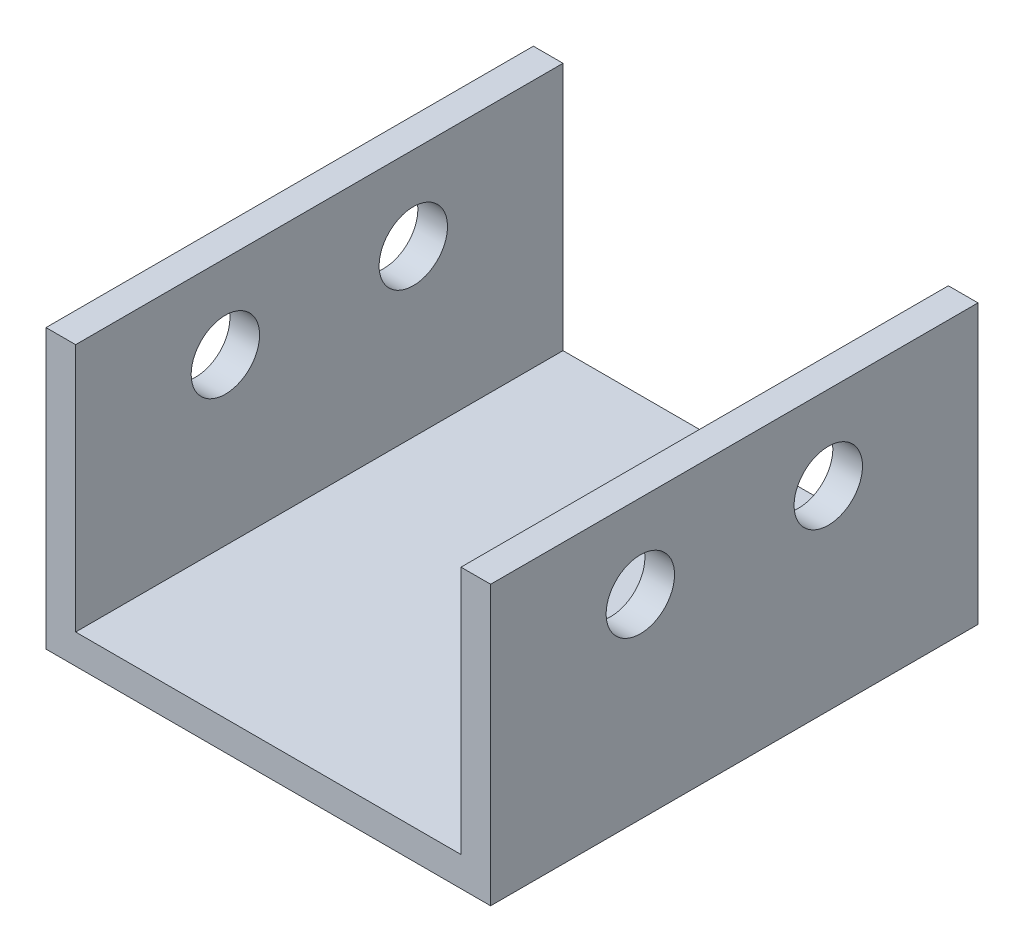
SolidWorks part; units mm, degrees
ref_plane "Front Plane" through (0, 0, 0) normal (0, 0, 1) x (1, 0, 0)
ref_plane "Top Plane" through (0, 0, 0) normal (0, 1, 0) x (1, 0, 0)
ref_plane "Right Plane" through (0, 0, 0) normal (1, 0, 0) x (0, 0, -1)
sketch "Sketch1" plane through (0, 0, 0) normal (0, 0, 1) x (1, 0, 0)
  line L0 (-26, 0) -> (26, 0)
  line L1 (26, 0) -> (26, 32.5714)
  line L2 (26, 32.5714) -> (22.5333, 32.5714)
  line L3 (22.5333, 32.5714) -> (22.5333, 3.4667)
  line L4 (22.5333, 3.4667) -> (-22.5333, 3.4667)
  line L5 (-22.5333, 3.4667) -> (-22.5333, 32.5714)
  line L6 (-22.5333, 32.5714) -> (-26, 32.5714)
  line L7 (-26, 32.5714) -> (-26, 0)
  line L9 (26, 0) -> (22.5333, 0) construction
  line L10 (26, 0) -> (26, 3.4667) construction
  line L11 (26, 3.4667) -> (22.5333, 3.4667) construction
  line L12 (22.5333, 0) -> (22.5333, 3.4667) construction
  point P4 (0, 0)
  dimension "D1" = 3.4667
  dimension "D2" = 32.5714
  dimension "D3" = 52
extrude "Boss-Extrude1" add sketch "Sketch1" along normal mid plane 57
sketch "Sketch2" plane through (26, 0, 0) normal (1, 0, 0) x (0, 0, -1)
  line L0 (0, 32.5714) -> (0, 0) construction
  line L1 (-28.5, 32.5714) -> (28.5, 32.5714) construction
  line L2 (-28.5, 0) -> (28.5, 0) construction
  line L3 (-28.5, 32.5714) -> (-28.5, 0) construction
  circle A0 centre (-10.99, 22.8) radius 10.99 construction
  circle A1 centre (-10.99, 22.8) radius 4
  circle A2 centre (10.99, 22.8) radius 4
  dimension "D2" = 32.5714
  dimension "D1" = 10.99
  dimension "D4" = 8
  dimension "D3" = 22.8
extrude "Cut-Extrude1" cut sketch "Sketch2" against normal through all
equation "\"D1@Sketch1\"=\"D3@Sketch1\"*0.2/3"
equation "\"D2@Sketch1\"=57*2/3.5"
equation "\"D3@Sketch2\"=\"D2@Sketch2\"*1.4/2"
